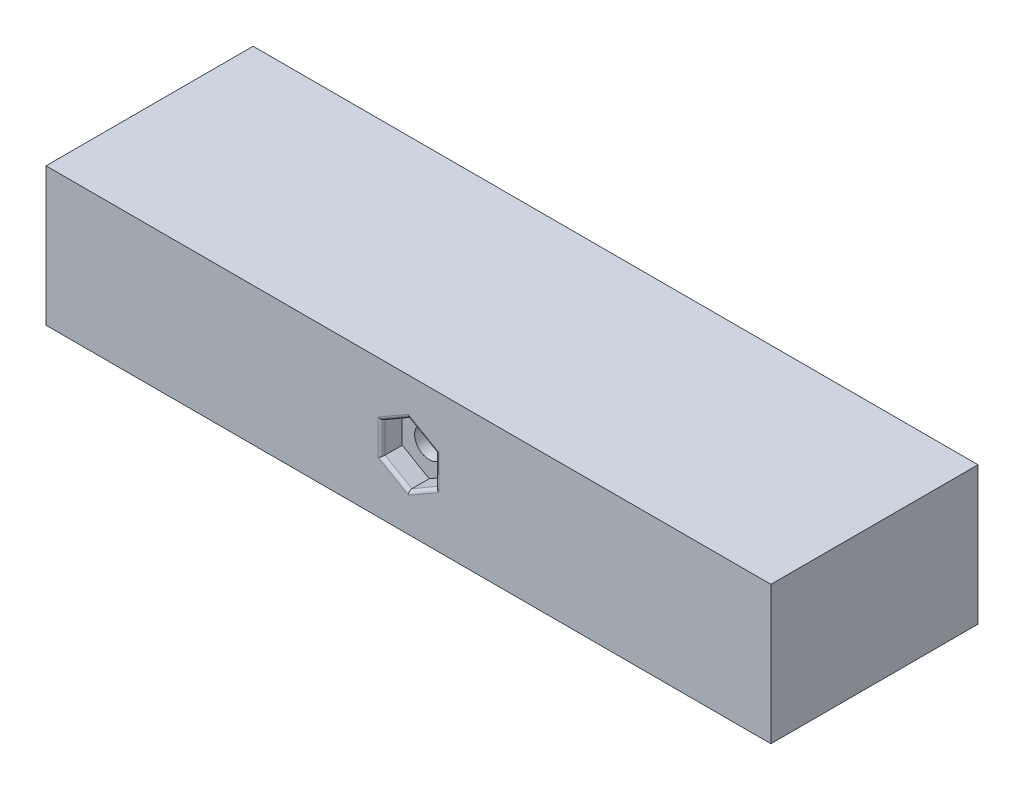
SolidWorks part; units mm, degrees
ref_plane "Plan de face" through (0, 0, 0) normal (0, 0, 1) x (1, 0, 0)
ref_plane "Plan de dessus" through (0, 0, 0) normal (0, 1, 0) x (1, 0, 0)
ref_plane "Plan de droite" through (0, 0, 0) normal (1, 0, 0) x (0, 0, -1)
sketch "Esquisse1" plane through (0, 0, 0) normal (0, 0, 1) x (1, 0, 0)
  line L1 (0, 0) -> (-105, 0)
  line L2 (0, 0) -> (0, 20)
  line L3 (0, 20) -> (-105, 20)
  line L4 (-105, 0) -> (-105, 20)
  dimension "D1" = 105
  dimension "D2" = 20
extrude "Boss.-Extru.1" add sketch "Esquisse1" along normal blind 30
sketch "Esquisse4" plane through (0, 0, 30) normal (0, 0, 1) x (1, 0, 0)
  line L0 (0, 20) -> (-105, 20) construction
  line L1 (-105, 20) -> (-105, 0) construction
  point P0 (-52.5, 20)
  point P1 (-105, 10)
sketch "Esquisse2" plane through (0, 0, 30) normal (0, 0, 1) x (1, 0, 0)
  line L0 (0, 0) -> (0, 20) construction
  line L1 (-52.5, 5.4967) -> (-48.6, 7.7483)
  line L2 (-48.6, 7.7483) -> (-48.6, 12.2517)
  line L3 (-48.6, 12.2517) -> (-52.5, 14.5033)
  line L4 (-52.5, 14.5033) -> (-56.4, 12.2517)
  line L5 (-56.4, 12.2517) -> (-56.4, 7.7483)
  line L6 (-56.4, 7.7483) -> (-52.5, 5.4967)
  circle A0 centre (-52.5, 10) radius 3.9 construction
  dimension "D1" = 7.8
extrude "Enlèv. mat.-Extru.1" cut sketch "Esquisse2" against normal blind 3
sketch "Esquisse3" plane through (0, 0, 30) normal (0, 0, 1) x (1, 0, 0)
  line L0 (0, 5) -> (0, 15) construction
  line L1 (-105, 15) -> (-105, 5) construction
  circle A0 centre (-10, 9.9745) radius 10
  circle A1 centre (-95, 9.9745) radius 9.9745
  dimension "D1" = 20
  dimension "D2" = 10
  dimension "D3" = 10
fillet "Congé2" radius 0.5 6 edges at (-56.4, 10, 30) (-54.45, 6.6225, 30) (-50.55, 6.6225, 30) (-48.6, 10, 30) (-50.55, 13.3775, 30) (-54.45, 13.3775, 30)
sketch "Esquisse8" plane through (0, 0, 0) normal (0, 0, 1) x (1, 0, 0)
  line L0 (0, 0) -> (0, 20) construction
  circle A0 centre (-52.5, 10) radius 2.1038
  dimension "D1" = 10
  dimension "D2" = 52.5
extrude "Enlèv. mat.-Extru.3" cut sketch "Esquisse8" along normal through all
sketch "Esquisse9" plane through (0, 0, 0) normal (0, -1, 0) x (1, 0, 0)
  line L0 (-105, 30) -> (0, 30) construction
  line L4 (0, 30) -> (0, 0) construction
  circle A0 centre (-52.5, 20) radius 2
  point P2 (-52.5, 30)
  dimension "D1" = 4
  dimension "D2" = 10
  dimension "D3" = 52.5
extrude "Enlèv. mat.-Extru.5" cut sketch "Esquisse9" against normal blind 5
sketch "Esquisse10" plane through (0, 0, 0) normal (0, -1, 0) x (1, 0, 0)
  line L0 (-105, 30) -> (-105, 0) construction
  line L1 (-25, 10) -> (-5, 10)
  line L2 (-25, 10) -> (-25, 5)
  line L3 (-25, 5) -> (-5, 5)
  line L4 (-5, 10) -> (-5, 5)
  line L5 (-11.39, 27.5) -> (-6.39, 27.5)
  line L6 (-11.39, 27.5) -> (-11.39, 12.5)
  line L7 (-11.39, 12.5) -> (-6.39, 12.5)
  line L8 (-6.39, 27.5) -> (-6.39, 12.5)
  line L9 (-98.61, 27.5) -> (-93.61, 27.5)
  line L10 (-98.61, 27.5) -> (-98.61, 12.5)
  line L11 (-98.61, 12.5) -> (-93.61, 12.5)
  line L12 (-93.61, 27.5) -> (-93.61, 12.5)
  line L13 (-100, 10) -> (-80, 10)
  line L14 (-100, 10) -> (-100, 5)
  line L15 (-100, 5) -> (-80, 5)
  line L16 (-80, 10) -> (-80, 5)
  line L17 (0, 30) -> (0, 0) construction
  line L18 (-105, 0) -> (0, 0) construction
  dimension "D1" = 5
  dimension "D2" = 5
  dimension "D3" = 20
  dimension "D4" = 5
  dimension "D5" = 15
  dimension "D6" = 2.5
  dimension "D7" = 5
  dimension "D8" = 5
  dimension "D9" = 20
  dimension "D10" = 2.5
  dimension "D11" = 5
  dimension "D12" = 15
  dimension "D13" = 1.39
  dimension "D14" = 5
  dimension "D15" = 5
  dimension "D16" = 1.39
extrude "Enlèv. mat.-Extru.6" cut sketch "Esquisse10" against normal blind 8
